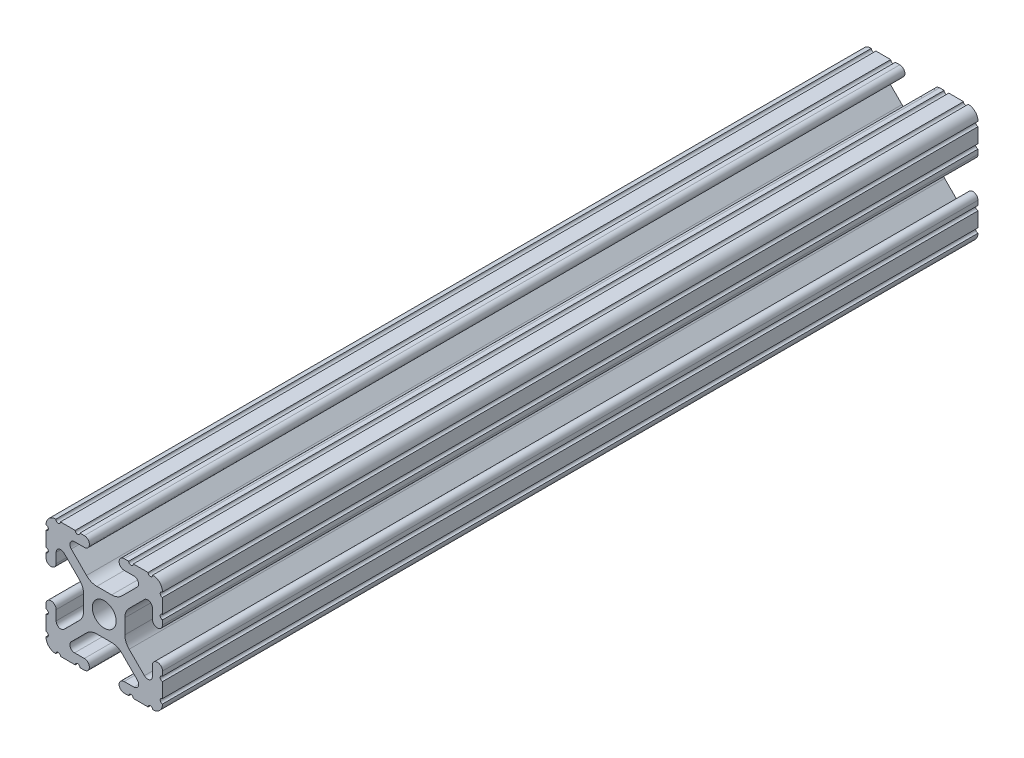
SolidWorks part; units mm, degrees
ref_plane "Front Plane" through (0, 0, 0) normal (0, 0, 1) x (1, 0, 0)
ref_plane "Top Plane" through (0, 0, 0) normal (0, 1, 0) x (1, 0, 0)
ref_plane "Right Plane" through (0, 0, 0) normal (1, 0, 0) x (0, 0, -1)
ref_plane "Plane1" through (0, 0, -1270) normal (0, 0, -1) x (-1, 0, 0)
sketch "Sketch1" plane through (0, 0, -1270) normal (0, 0, -1) x (-1, 0, 0)
  line L0 (12.7, -9.5504) -> (12.7, -6.3331)
  line L1 (12.7, -5.3171) -> (12.7, -4.3434)
  line L2 (10.4902, -4.3434) -> (10.4902, -6.4748)
  line L3 (8.7558, -7.1932) -> (5.4257, -3.8632)
  line L4 (4.4958, -1.6181) -> (4.4958, 1.6181)
  line L5 (5.4257, 3.8632) -> (8.7558, 7.1932)
  line L6 (10.4902, 6.4748) -> (10.4902, 4.3434)
  line L7 (12.7, 4.3434) -> (12.7, 5.3171)
  line L8 (12.7, 6.3331) -> (12.7, 9.5504)
  line L9 (9.5504, 12.7) -> (6.3331, 12.7)
  line L10 (5.3171, 12.7) -> (4.3434, 12.7)
  line L11 (4.3434, 10.4902) -> (6.4748, 10.4902)
  line L12 (7.1932, 8.7558) -> (3.8632, 5.4257)
  line L13 (1.6181, 4.4958) -> (-1.6181, 4.4958)
  line L14 (-3.8632, 5.4257) -> (-7.1932, 8.7558)
  line L15 (-6.4748, 10.4902) -> (-4.3434, 10.4902)
  line L16 (-4.3434, 12.7) -> (-5.3171, 12.7)
  line L17 (-6.3331, 12.7) -> (-9.5504, 12.7)
  line L18 (-12.7, 9.5504) -> (-12.7, 6.3331)
  line L19 (-12.7, 5.3171) -> (-12.7, 4.3434)
  line L20 (-10.4902, 4.3434) -> (-10.4902, 6.4748)
  line L21 (-8.7558, 7.1932) -> (-5.4257, 3.8632)
  line L22 (-4.4958, 1.6181) -> (-4.4958, -1.6181)
  line L23 (-5.4257, -3.8632) -> (-8.7558, -7.1932)
  line L24 (-10.4902, -6.4748) -> (-10.4902, -4.3434)
  line L25 (-12.7, -4.3434) -> (-12.7, -5.3171)
  line L26 (-12.7, -6.3331) -> (-12.7, -9.5504)
  line L27 (-9.5504, -12.7) -> (-6.3331, -12.7)
  line L28 (-5.3171, -12.7) -> (-4.3434, -12.7)
  line L29 (-4.3434, -10.4902) -> (-6.4748, -10.4902)
  line L30 (-7.1932, -8.7558) -> (-3.8632, -5.4257)
  line L31 (-1.6181, -4.4958) -> (1.6181, -4.4958)
  line L32 (3.8632, -5.4257) -> (7.1932, -8.7558)
  line L33 (6.4748, -10.4902) -> (4.3434, -10.4902)
  line L34 (4.3434, -12.7) -> (5.3171, -12.7)
  line L35 (6.3331, -12.7) -> (9.5504, -12.7)
  circle A0 centre (0, 0) radius 2.6035
  arc A1 (12.7, -6.3331) -> (12.7, -5.3171) centre (12.7, -5.8251) cw
  arc A2 (12.7, -4.3434) -> (10.4902, -4.3434) centre (11.5951, -4.3434) ccw
  arc A3 (10.4902, -6.4748) -> (8.7558, -7.1932) centre (9.4742, -6.4748) cw
  arc A4 (5.4257, -3.8632) -> (4.4958, -1.6181) centre (7.6708, -1.6181) cw
  arc A5 (4.4958, 1.6181) -> (5.4257, 3.8632) centre (7.6708, 1.6181) cw
  arc A6 (8.7558, 7.1932) -> (10.4902, 6.4748) centre (9.4742, 6.4748) cw
  arc A7 (10.4902, 4.3434) -> (12.7, 4.3434) centre (11.5951, 4.3434) ccw
  arc A8 (12.7, 5.3171) -> (12.7, 6.3331) centre (12.7, 5.8251) cw
  arc A9 (12.7, 9.5504) -> (12.6998, 10.5664) centre (12.7, 10.0584) cw
  arc A10 (12.6998, 10.5664) -> (10.5664, 12.6998) centre (10.5918, 10.5918) ccw
  arc A11 (10.5664, 12.6998) -> (9.5504, 12.7) centre (10.0584, 12.7) cw
  arc A12 (6.3331, 12.7) -> (5.3171, 12.7) centre (5.8251, 12.7) cw
  arc A13 (4.3434, 12.7) -> (4.3434, 10.4902) centre (4.3434, 11.5951) ccw
  arc A14 (6.4748, 10.4902) -> (7.1932, 8.7558) centre (6.4748, 9.4742) cw
  arc A15 (3.8632, 5.4257) -> (1.6181, 4.4958) centre (1.6181, 7.6708) cw
  arc A16 (-1.6181, 4.4958) -> (-3.8632, 5.4257) centre (-1.6181, 7.6708) cw
  arc A17 (-7.1932, 8.7558) -> (-6.4748, 10.4902) centre (-6.4748, 9.4742) cw
  arc A18 (-4.3434, 10.4902) -> (-4.3434, 12.7) centre (-4.3434, 11.5951) ccw
  arc A19 (-5.3171, 12.7) -> (-6.3331, 12.7) centre (-5.8251, 12.7) cw
  arc A20 (-9.5504, 12.7) -> (-10.5664, 12.6998) centre (-10.0584, 12.7) cw
  arc A21 (-10.5664, 12.6998) -> (-12.6998, 10.5664) centre (-10.5918, 10.5918) ccw
  arc A22 (-12.6998, 10.5664) -> (-12.7, 9.5504) centre (-12.7, 10.0584) cw
  arc A23 (-12.7, 6.3331) -> (-12.7, 5.3171) centre (-12.7, 5.8251) cw
  arc A24 (-12.7, 4.3434) -> (-10.4902, 4.3434) centre (-11.5951, 4.3434) ccw
  arc A25 (-10.4902, 6.4748) -> (-8.7558, 7.1932) centre (-9.4742, 6.4748) cw
  arc A26 (-5.4257, 3.8632) -> (-4.4958, 1.6181) centre (-7.6708, 1.6181) cw
  arc A27 (-4.4958, -1.6181) -> (-5.4257, -3.8632) centre (-7.6708, -1.6181) cw
  arc A28 (-8.7558, -7.1932) -> (-10.4902, -6.4748) centre (-9.4742, -6.4748) cw
  arc A29 (-10.4902, -4.3434) -> (-12.7, -4.3434) centre (-11.5951, -4.3434) ccw
  arc A30 (-12.7, -5.3171) -> (-12.7, -6.3331) centre (-12.7, -5.8251) cw
  arc A31 (-12.7, -9.5504) -> (-12.6998, -10.5664) centre (-12.7, -10.0584) cw
  arc A32 (-12.6998, -10.5664) -> (-10.5664, -12.6998) centre (-10.5918, -10.5918) ccw
  arc A33 (-10.5664, -12.6998) -> (-9.5504, -12.7) centre (-10.0584, -12.7) cw
  arc A34 (-6.3331, -12.7) -> (-5.3171, -12.7) centre (-5.8251, -12.7) cw
  arc A35 (-4.3434, -12.7) -> (-4.3434, -10.4902) centre (-4.3434, -11.5951) ccw
  arc A36 (-6.4748, -10.4902) -> (-7.1932, -8.7558) centre (-6.4748, -9.4742) cw
  arc A37 (-3.8632, -5.4257) -> (-1.6181, -4.4958) centre (-1.6181, -7.6708) cw
  arc A38 (1.6181, -4.4958) -> (3.8632, -5.4257) centre (1.6181, -7.6708) cw
  arc A39 (7.1932, -8.7558) -> (6.4748, -10.4902) centre (6.4748, -9.4742) cw
  arc A40 (4.3434, -10.4902) -> (4.3434, -12.7) centre (4.3434, -11.5951) ccw
  arc A41 (5.3171, -12.7) -> (6.3331, -12.7) centre (5.8251, -12.7) cw
  arc A42 (9.5504, -12.7) -> (10.5664, -12.6998) centre (10.0584, -12.7) cw
  arc A43 (10.5664, -12.6998) -> (12.6998, -10.5664) centre (10.5918, -10.5918) ccw
  arc A44 (12.6998, -10.5664) -> (12.7, -9.5504) centre (12.7, -10.0584) cw
extrude "Boss-Extrude1" add sketch "Sketch1" against normal blind 1270
ref_plane "Plane2" through (0, 0, -698.5) normal (0, 0, -1) x (-1, 0, 0)
sketch "Sketch6" plane through (0, 0, -698.5) normal (0, 0, -1) x (-1, 0, 0)
  line L0 (79.0024, -75.2236) -> (-43.6645, -75.2236)
  line L1 (79.0024, -75.2236) -> (79.0024, 34.1242)
  line L2 (79.0024, 34.1242) -> (-43.6645, 34.1242)
  line L3 (-43.6645, -75.2236) -> (-43.6645, 34.1242)
extrude "Cut-Extrude1" cut sketch "Sketch6" along normal through all
sketch "Sketch7" plane through (0, 0, 0) normal (0, 0, 1) x (1, 0, 0)
  line L1 (14.8387, -13.8646) -> (-14.8387, -13.8646)
  line L2 (14.8387, -13.8646) -> (14.8387, 13.8646)
  line L3 (14.8387, 13.8646) -> (-14.8387, 13.8646)
  line L4 (-14.8387, -13.8646) -> (-14.8387, 13.8646)
  line L5 (14.8387, -13.8646) -> (-14.8387, 13.8646) construction
  line L6 (14.8387, 13.8646) -> (-14.8387, -13.8646) construction
  point P0 (0, 0)
extrude "Cut-Extrude2" cut sketch "Sketch7" against normal blind 520.7
